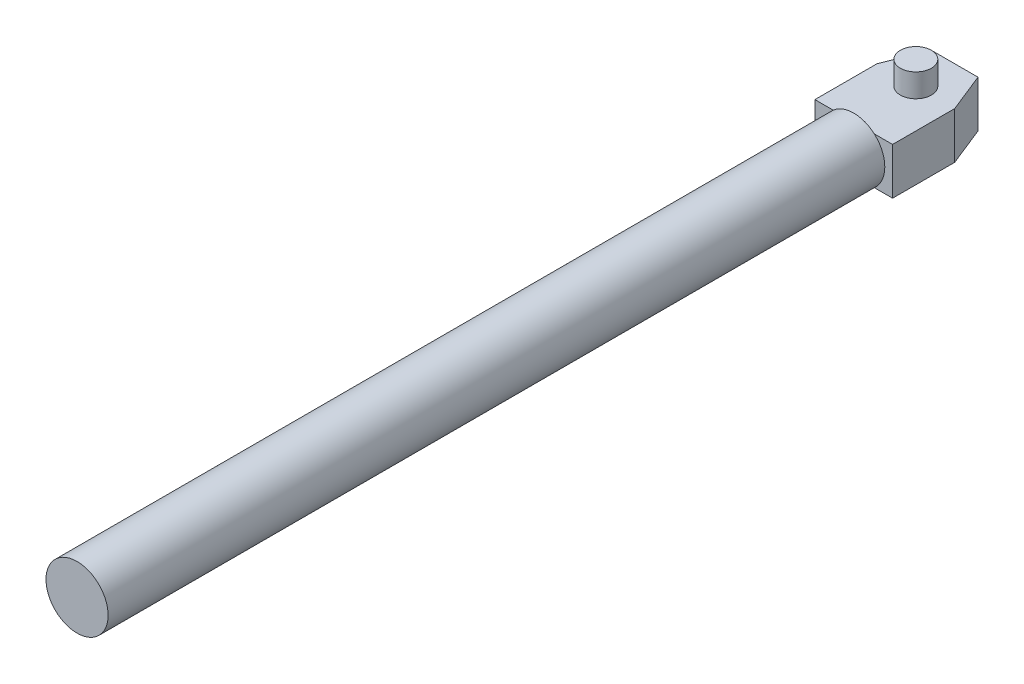
SolidWorks part; units mm, degrees
ref_plane "Front Plane" through (0, 0, 0) normal (0, 0, 1) x (1, 0, 0)
ref_plane "Top Plane" through (0, 0, 0) normal (0, 1, 0) x (1, 0, 0)
ref_plane "Right Plane" through (0, 0, 0) normal (1, 0, 0) x (0, 0, -1)
sketch "Sketch1" plane through (0, 0, 0) normal (0, 0, 1) x (1, 0, 0)
  circle A0 centre (0, 0) radius 20
  dimension "D1" = 40
extrude "Boss-Extrude1" add sketch "Sketch1" along normal blind 500
sketch "Sketch2" plane through (0, 0, 0) normal (0, 1, 0) x (1, 0, 0)
  line L0 (-25, 40) -> (-15, 65)
  line L1 (-25, 0) -> (25, 0)
  line L2 (-25, 0) -> (-25, 40)
  line L3 (-15, 65) -> (15, 65)
  line L4 (25, 0) -> (25, 40)
  line L5 (15, 65) -> (25, 40)
  point P1 (25, 65)
  point P2 (-25, 65)
  dimension "D1" = 50
  dimension "D2" = 65
  dimension "D3" = 25
  dimension "D4" = 10
  dimension "D5" = 10
  dimension "D6" = 25
extrude "Boss-Extrude2" add sketch "Sketch2" along normal mid plane 30
sketch "Sketch4" plane through (0, 0, 0) normal (0, 1, 0) x (1, 0, 0)
  line L0 (-13.2288, 0) -> (13.2288, 0) construction
  circle A0 centre (0, 40) radius 10
  dimension "D1" = 20
  dimension "D2" = 40
extrude "Boss-Extrude3" add sketch "Sketch4" along normal mid plane 60
